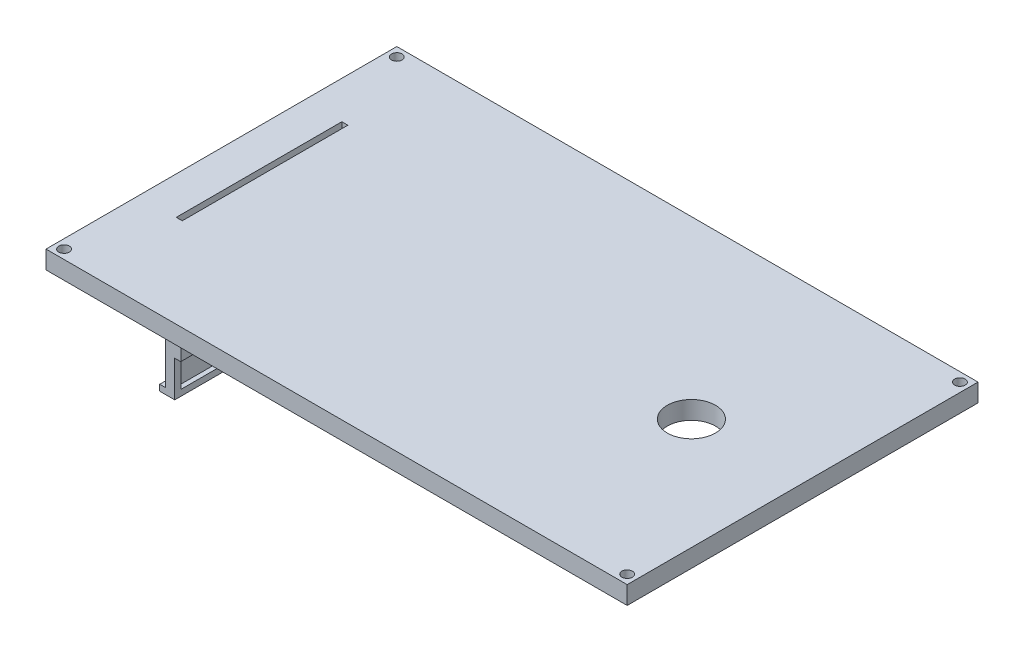
SolidWorks part; units mm, degrees
ref_plane "Front Plane" through (0, 0, 0) normal (0, 0, 1) x (1, 0, 0)
ref_plane "Top Plane" through (0, 0, 0) normal (0, 1, 0) x (1, 0, 0)
ref_plane "Right Plane" through (0, 0, 0) normal (1, 0, 0) x (0, 0, -1)
sketch "Sketch1" plane through (0, 0, 0) normal (0, 1, 0) x (1, 0, 0)
  line L1 (-73.6202, 41.1716) -> (119.3798, 41.1716)
  line L2 (-73.6202, 41.1716) -> (-73.6202, -75.3284)
  line L3 (-73.6202, -75.3284) -> (119.3798, -75.3284)
  line L4 (119.3798, 41.1716) -> (119.3798, -75.3284)
  line L13 (-48.3313, 10.4216) -> (-46.3313, 10.4216)
  line L14 (-48.3313, 10.4216) -> (-48.3313, -44.5784)
  line L15 (-48.3313, -44.5784) -> (-46.3313, -44.5784)
  line L16 (-46.3313, 10.4216) -> (-46.3313, -44.5784)
  circle A4 centre (-70.6202, -72.3284) radius 1.75
  circle A5 centre (-70.6202, 38.1716) radius 1.75
  circle A6 centre (116.3798, -72.3284) radius 1.75
  circle A7 centre (116.3798, 38.1716) radius 1.75
  circle A8 centre (82.4507, -17.0784) radius 8
  dimension "D3" = 16
  dimension "D1" = 193
  dimension "D2" = 116.5
  dimension "D4" = 58.25
  dimension "D9" = 55
  dimension "D10" = 2
  dimension "D11" = 30.75
  dimension "D16" = 3
  dimension "D17" = 3
  dimension "D18" = 3
  dimension "D19" = 3
extrude "Boss-Extrude1" add sketch "Sketch1" along normal blind 6
sketch "Sketch3" plane through (0, 0, 0) normal (0, -1, 0) x (1, 0, 0)
  line L0 (-73.6202, 75.3284) -> (119.3798, 75.3284) construction
  line L1 (-67.6202, 69.3284) -> (-57.6202, 69.3284)
  line L2 (-67.6202, 69.3284) -> (-67.6202, 59.3284)
  line L3 (-67.6202, 59.3284) -> (-57.6202, 59.3284)
  line L4 (-57.6202, 69.3284) -> (-57.6202, 59.3284)
  line L5 (-73.6202, -41.1716) -> (-73.6202, 75.3284) construction
  line L6 (-67.6202, -25.1716) -> (-57.6202, -25.1716)
  line L7 (-67.6202, -25.1716) -> (-67.6202, -35.1716)
  line L8 (-67.6202, -35.1716) -> (-57.6202, -35.1716)
  line L9 (-57.6202, -25.1716) -> (-57.6202, -35.1716)
  line L10 (119.3798, -41.1716) -> (-73.6202, -41.1716) construction
  line L11 (103.3798, -25.1716) -> (113.3798, -25.1716)
  line L12 (103.3798, -25.1716) -> (103.3798, -35.1716)
  line L13 (103.3798, -35.1716) -> (113.3798, -35.1716)
  line L14 (113.3798, -25.1716) -> (113.3798, -35.1716)
  line L15 (119.3798, 75.3284) -> (119.3798, -41.1716) construction
  line L16 (103.3798, 69.3284) -> (113.3798, 69.3284)
  line L17 (103.3798, 69.3284) -> (103.3798, 59.3284)
  line L18 (103.3798, 59.3284) -> (113.3798, 59.3284)
  line L19 (113.3798, 69.3284) -> (113.3798, 59.3284)
  dimension "D1" = 10
  dimension "D2" = 10
  dimension "D3" = 6
  dimension "D4" = 6
  dimension "D5" = 6
  dimension "D6" = 6
  dimension "D7" = 6
  dimension "D8" = 6
  dimension "D9" = 6
  dimension "D10" = 6
  dimension "D11" = 10
  dimension "D12" = 10
  dimension "D13" = 10
  dimension "D14" = 10
  dimension "D15" = 10
  dimension "D16" = 10
extrude "Boss-Extrude3" add sketch "Sketch3" along normal blind 10
sketch "Sketch5" plane through (0, 0, 0) normal (0, -1, 0) x (1, 0, 0)
  line L1 (-48.3313, 44.5784) -> (-46.3313, 44.5784)
  line L2 (-48.3313, 44.5784) -> (-48.3313, -10.4216)
  line L3 (-48.3313, -10.4216) -> (-46.3313, -10.4216)
  line L4 (-46.3313, 44.5784) -> (-46.3313, -10.4216)
extrude "Boss-Extrude4" add sketch "Sketch5" against normal blind 6
sketch "Sketch6" plane through (0, -10, 0) normal (0, -1, 0) x (1, 0, 0)
  line L1 (-67.6202, 69.3284) -> (113.3798, 69.3284)
  line L2 (-67.6202, 69.3284) -> (-67.6202, -35.1716)
  line L3 (-67.6202, -35.1716) -> (113.3798, -35.1716)
  line L4 (113.3798, 69.3284) -> (113.3798, -35.1716)
extrude "Cut-Extrude1" cut sketch "Sketch6" against normal blind 4
sketch "Sketch7" plane through (0, 0, 0) normal (0, -1, 0) x (1, 0, 0)
  line L0 (119.3798, -41.1716) -> (-73.6202, -41.1716) construction
  line L1 (-62.6202, 44.5784) -> (-61.1202, 44.5784)
  line L2 (-62.6202, 44.5784) -> (-62.6202, -10.4216)
  line L3 (-62.6202, -10.4216) -> (-61.1202, -10.4216)
  line L4 (-61.1202, 44.5784) -> (-61.1202, -10.4216)
  line L6 (-73.6202, -41.1716) -> (-73.6202, 75.3284) construction
  dimension "D1" = 55
  dimension "D2" = 1.5
  dimension "D3" = 30.75
  dimension "D4" = 11
extrude "Boss-Extrude5" add sketch "Sketch7" along normal blind 44.75
sketch "Sketch8" plane through (0, 0, 0) normal (0, -1, 0) x (1, 0, 0)
  line L1 (-61.1202, 44.5784) -> (-59.1202, 44.5784)
  line L2 (-61.1202, 44.5784) -> (-61.1202, -10.4216)
  line L3 (-61.1202, -10.4216) -> (-59.1202, -10.4216)
  line L4 (-59.1202, 44.5784) -> (-59.1202, -10.4216)
  dimension "D1" = 55
  dimension "D2" = 2
extrude "Cut-Extrude2" cut sketch "Sketch8" against normal blind 42.25
fillet "Fillet3" radius 3 16 edges at (-62.6202, -6, -35.1716) (-67.6202, -6, -30.1716) (-62.6202, -6, -25.1716) (-57.6202, -6, -30.1716) (-67.6202, -6, 64.3284) (-62.6202, -6, 69.3284) (-57.6202, -6, 64.3284) (-62.6202, -6, 59.3284) (108.3798, -6, 69.3284) (113.3798, -6, 64.3284) (108.3798, -6, 59.3284) (103.3798, -6, 64.3284) (108.3798, -6, -25.1716) (113.3798, -6, -30.1716) (108.3798, -6, -35.1716) (103.3798, -6, -30.1716)
sketch "Sketch12" plane through (-61.1202, 0, 0) normal (1, 0, 0) x (0, 0, -1)
  line L0 (10.4216, -44.75) -> (10.4216, 0) construction
  line L1 (-44.5784, -44.75) -> (10.4216, -44.75)
  line L2 (-44.5784, -44.75) -> (-44.5784, -42.75)
  line L3 (-44.5784, -42.75) -> (10.4216, -42.75)
  line L4 (10.4216, -44.75) -> (10.4216, -42.75)
  dimension "D1" = 2
extrude "Boss-Extrude6" add sketch "Sketch12" along normal blind 1.5
sketch "Sketch14" plane through (0, 0, -10.4216) normal (0, 0, -1) x (-1, 0, 0)
  line L1 (59.6202, -44.75) -> (62.6202, -44.75)
  line L2 (59.6202, -44.75) -> (59.6202, 0)
  line L3 (59.6202, 0) -> (62.6202, 0)
  line L4 (62.6202, -44.75) -> (62.6202, 0)
  point P0 (59.6202, -44.75)
  point P1 (62.6202, 0)
extrude "Boss-Extrude7" add sketch "Sketch14" along normal blind 2
sketch "Sketch15" plane through (0, 0, 44.5784) normal (0, 0, 1) x (1, 0, 0)
  line L1 (-62.6202, 0) -> (-59.6202, 0)
  line L2 (-62.6202, 0) -> (-62.6202, -44.75)
  line L3 (-62.6202, -44.75) -> (-59.6202, -44.75)
  line L4 (-59.6202, 0) -> (-59.6202, -44.75)
  point P0 (-59.6202, -44.75)
  point P1 (-62.6202, 0)
extrude "Boss-Extrude8" add sketch "Sketch15" along normal blind 2
sketch "Sketch16" plane through (-62.6202, 0, 0) normal (-1, 0, 0) x (0, 0, 1)
  line L0 (46.5784, 0) -> (-12.4216, 0) construction
  line L2 (-10.4216, 0) -> (-10.4216, -42.75)
  line L3 (-10.4216, -42.75) -> (46.5784, -42.75)
  line L5 (46.5784, 0) -> (46.5784, -44.75) construction
  line L6 (-12.4216, -44.75) -> (-12.4216, 0) construction
  line L7 (46.5784, -44.75) -> (-12.4216, -44.75) construction
  line L8 (-10.4216, 0) -> (-12.4216, 0)
  line L9 (-12.4216, 0) -> (-12.4216, -44.75)
  line L10 (-12.4216, -44.75) -> (46.5784, -44.75)
  line L11 (46.5784, -44.75) -> (46.5784, -42.75)
  dimension "D1" = 2
  dimension "D2" = 2
extrude "Boss-Extrude9" add sketch "Sketch16" along normal blind 2 contours L2 L3 L11 L10 L9 L8
sketch "Sketch18" plane through (-59.6202, 0, 0) normal (1, 0, 0) x (0, 0, -1)
  line L0 (-46.5784, -44.75) -> (-46.5784, 0) construction
  line L1 (-46.5784, 0) -> (-26.5784, 0)
  line L2 (-46.5784, 0) -> (-46.5784, -32.75)
  line L3 (-46.5784, -32.75) -> (-26.5784, -32.75)
  line L4 (12.4216, 0) -> (12.4216, -32.75)
  line L5 (12.4216, 0) -> (12.4216, -44.75) construction
  line L7 (-75.3284, 0) -> (41.1716, 0) construction
  line L8 (-46.5784, -44.75) -> (12.4216, -44.75) construction
  line L9 (-26.5784, -32.75) -> (-26.5784, 0)
  line L10 (-7.5784, -32.75) -> (-7.5784, 0)
  line L11 (-7.5784, -32.75) -> (12.4216, -32.75)
  line L12 (-7.5784, 0) -> (12.4216, 0)
  dimension "D1" = 0
  dimension "D2" = 12
  dimension "D3" = 20
  dimension "D4" = 20
extrude "Boss-Extrude10" add sketch "Sketch18" along normal blind 2
